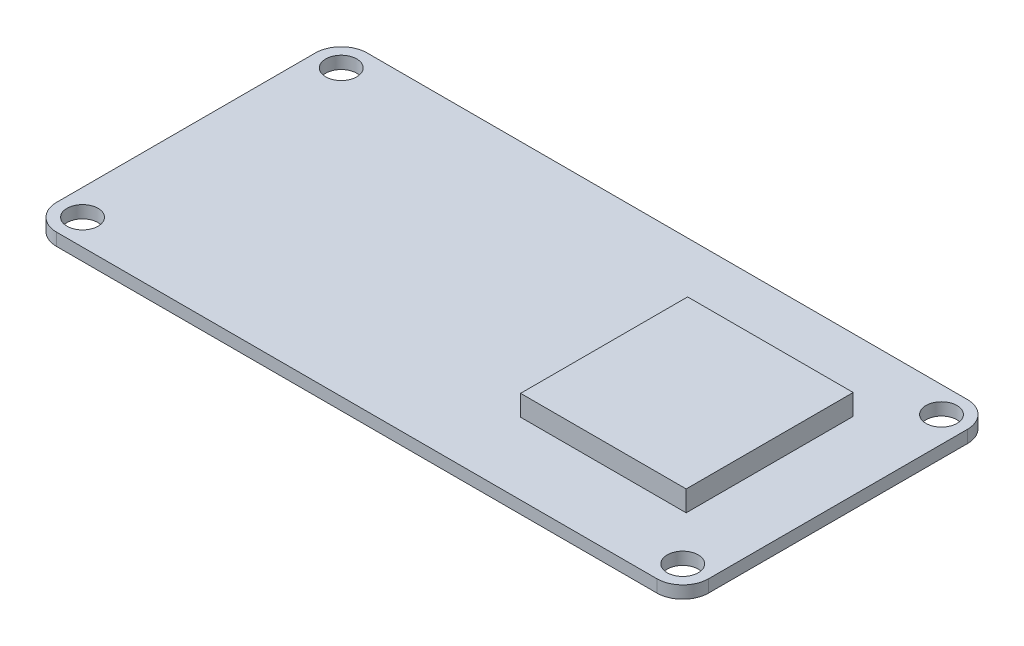
SolidWorks part; units mm, degrees
ref_plane "Front Plane" through (0, 0, 0) normal (0, 0, 1) x (1, 0, 0)
ref_plane "Top Plane" through (0, 0, 0) normal (0, 1, 0) x (1, 0, 0)
ref_plane "Right Plane" through (0, 0, 0) normal (1, 0, 0) x (0, 0, -1)
sketch "Sketch1" plane through (0, 0, 0) normal (0, 1, 0) x (1, 0, 0)
  line L1 (-29.0728, 13.6873) -> (33.9272, 13.6873)
  line L2 (-29.0728, 13.6873) -> (-29.0728, -16.3127)
  line L3 (-29.0728, -16.3127) -> (33.9272, -16.3127)
  line L4 (33.9272, 13.6873) -> (33.9272, -16.3127)
  circle A0 centre (-26.5728, 11.1873) radius 1.5
  circle A1 centre (-26.5728, -13.8127) radius 1.5
  circle A2 centre (31.4272, -13.8127) radius 1.5
  circle A3 centre (31.4272, 11.1873) radius 1.5
  dimension "D3" = 3
  dimension "D6" = 3
  dimension "D7" = 3
  dimension "D8" = 3
  dimension "D1" = 2.5
  dimension "D2" = 2.5
  dimension "D4" = 63
  dimension "D5" = 30
  dimension "D9" = 2.5
  dimension "D10" = 2.5
  dimension "D11" = 2.5
  dimension "D12" = 2.5
  dimension "D13" = 2.5
  dimension "D14" = 2.5
extrude "Boss-Extrude1" add sketch "Sketch1" along normal blind 1.2 contours L2 L1 L4 L3
fillet "Fillet1" radius 2.5 4 edges at (33.9272, 0.6, -13.6873) (33.9272, 0.6, 16.3127) (-29.0728, 0.6, 16.3127) (-29.0728, 0.6, -13.6873)
sketch "Sketch2" plane through (0, 1.2, 0) normal (0, 1, 0) x (1, 0, 0)
  line L0 (33.9272, -13.8127) -> (33.9272, 11.1873) construction
  line L1 (11.3272, 6.7574) -> (27.3272, 6.7574)
  line L2 (11.3272, 6.7574) -> (11.3272, -9.3828)
  line L3 (11.3272, -9.3828) -> (27.3272, -9.3828)
  line L4 (27.3272, 6.7574) -> (27.3272, -9.3828)
  dimension "D1" = 16.1402
  dimension "D2" = 22.6
  dimension "D3" = 16
extrude "Boss-Extrude2" add sketch "Sketch2" along normal blind 2
